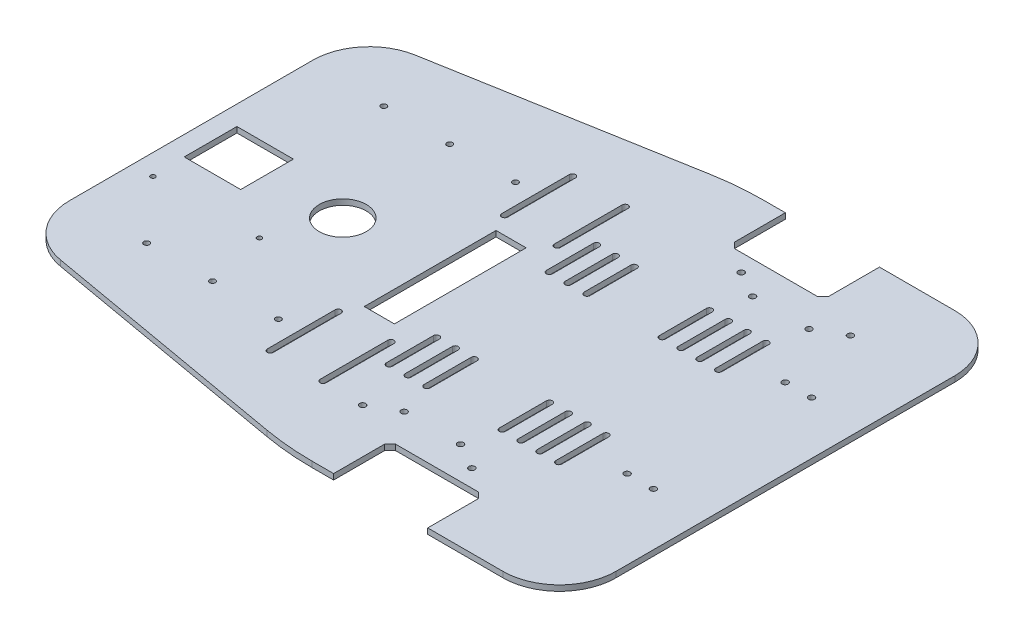
SolidWorks part; units mm, degrees
ref_plane "前视基准面" through (0, 0, 0) normal (0, 0, 1) x (1, 0, 0)
ref_plane "上视基准面" through (0, 0, 0) normal (0, 1, 0) x (1, 0, 0)
ref_plane "右视基准面" through (0, 0, 0) normal (1, 0, 0) x (0, 0, -1)
other "Configuration Table"
sketch "草图1" plane through (0, 0, 0) normal (0, 1, 0) x (1, 0, 0)
  line L0 (40, 120) -> (40, -12.8004) construction
  line L1 (15.3051, 120) -> (130, 120)
  line L2 (-155.7144, 64.6716) -> (-155.7144, -64.6716)
  line L3 (15.3051, -120) -> (130, -120)
  line L4 (160, 90) -> (160, -90)
  line L5 (-160, 120) -> (160, -120) construction
  line L6 (-160, -120) -> (160, 120) construction
  line L7 (15.3051, 120) -> (-130.9239, 94.2159)
  line L8 (-96.2123, 0) -> (107.3836, 0) construction
  line L9 (15.3051, -120) -> (-130.9239, -94.2159)
  arc A0 (130, -120) -> (160, -90) centre (130, -90) ccw
  arc A1 (160, 90) -> (130, 120) centre (130, 90) ccw
  arc A2 (-130.9239, -94.2159) -> (-155.7144, -64.6716) centre (-125.7144, -64.6716) cw
  arc A3 (-155.7144, 64.6716) -> (-130.9239, 94.2159) centre (-125.7144, 64.6716) cw
  point P0 (0, 0)
  point P22 (-155.7144, -89.8446)
  point P25 (-155.7144, 89.8446)
  dimension "D3" = 30
  dimension "D6" = 30
  dimension "D1" = 320
  dimension "D2" = 240
  dimension "D4" = 120
  dimension "D5" = 10
extrude "凸台-拉伸1" add sketch "草图1" along normal blind 3
sketch "草图2" plane through (0, 3, 0) normal (0, 1, 0) x (1, 0, 0)
  line L0 (65, 124.0473) -> (65, -125.6765) construction
  line L1 (160, -90) -> (160, 90) construction
  line L2 (40, -90) -> (90, -90)
  line L4 (15.3051, -120) -> (130, -120) construction
  line L5 (40, -90) -> (40, -120)
  line L6 (40, -120) -> (90, -120)
  line L7 (90, -120) -> (90, -90)
  line L8 (-190.597, 0) -> (207.9466, 0) construction
  line L9 (40, 120) -> (90, 120)
  line L10 (90, 120) -> (90, 90)
  line L11 (40, 90) -> (90, 90)
  line L12 (40, 90) -> (40, 120)
  point P8 (65, -90)
  dimension "D1" = 95
  dimension "D2" = 50
  dimension "D3" = 30
extrude "切除-拉伸1" cut sketch "草图2" against normal through all
chamfer "倒角1" distance 3 angle 45 4 edges at (90, 1.5, -90) (40, 1.5, -90) (90, 1.5, 90) (40, 1.5, 90)
sketch "草图3" plane through (0, 3, 0) normal (0, 1, 0) x (1, 0, 0)
  line L0 (87, -90) -> (43, -90) construction
  line L1 (90, -120) -> (90, -93) construction
  line L2 (45.23, -47.1241) -> (45.23, -105.6682) construction
  line L3 (40, 120) -> (40, 93) construction
  line L4 (43, 90) -> (87, 90) construction
  line L5 (84.77, 111.6004) -> (84.77, 44.6968) construction
  circle A0 centre (74.23, -80.8) radius 1.6
  circle A1 centre (60.23, -72.8) radius 1.6
  circle A2 centre (16.23, -80.8) radius 1.6
  circle A3 centre (30.23, -72.8) radius 1.6
  circle A4 centre (55.77, 80.8) radius 1.6
  circle A5 centre (69.77, 72.8) radius 1.6
  circle A6 centre (99.77, 72.8) radius 1.6
  circle A7 centre (113.77, 80.8) radius 1.6
  dimension "D1" = 9.2
  dimension "D3" = 8
  dimension "D6" = 15.77
  dimension "D8" = 14
  dimension "D2" = 15.77
  dimension "D4" = 14
  dimension "D5" = 15
  dimension "D7" = 9.2
  dimension "D9" = 8
  dimension "D10" = 15
extrude "切除-拉伸2" cut sketch "草图3" against normal through all
fillet "圆角3" radius 150 2 edges at (15.3051, 1.5, 120) (15.3051, 1.5, -120)
sketch "草图6" plane through (0, 3, 0) normal (0, 1, 0) x (1, 0, 0)
  circle A0 centre (132, 41.9099) radius 1.6 construction
  circle A1 centre (118, 41.9099) radius 1.6 construction
  circle A2 centre (132, -42.0901) radius 1.6 construction
  circle A3 centre (118, -42.0901) radius 1.6 construction
  circle A10 centre (132, 41.9099) radius 1.6
  circle A11 centre (118, 41.9099) radius 1.6
  circle A12 centre (132, -42.0901) radius 1.6
  circle A13 centre (118, -42.0901) radius 1.6
extrude "切除-拉伸3" cut sketch "草图6" against normal up to next
sketch "草图8" plane through (0, 0, 0) normal (0, -1, 0) x (1, 0, 0)
  circle A0 centre (-115.7144, -62.381) radius 1.5 construction
  circle A1 centre (-80.7144, -62.381) radius 1.5 construction
  circle A2 centre (-45.7144, -62.381) radius 1.5 construction
  circle A3 centre (-45.7144, 63.619) radius 1.5 construction
  circle A4 centre (-80.7144, 63.619) radius 1.5 construction
  circle A5 centre (-115.7144, 63.619) radius 1.5 construction
  circle A6 centre (-115.7144, -62.381) radius 1.5
  circle A7 centre (-80.7144, -62.381) radius 1.5
  circle A8 centre (-45.7144, -62.381) radius 1.5
  circle A9 centre (-45.7144, 63.619) radius 1.5
  circle A10 centre (-80.7144, 63.619) radius 1.5
  circle A11 centre (-115.7144, 63.619) radius 1.5
extrude "切除-拉伸5" cut sketch "草图8" against normal up to next
sketch "草图11" plane through (0, 0, 0) normal (0, -1, 0) x (1, 0, 0)
  line L0 (-136.2017, 0) -> (170.3375, 0) construction
  line L1 (84.6466, 55) -> (84.6466, 30) construction
  line L2 (86.2466, 55) -> (86.2466, 30)
  line L3 (83.0466, 55) -> (83.0466, 30)
  line L4 (74.6466, 55) -> (74.6466, 30) construction
  line L5 (44.6466, 64.0776) -> (44.6466, 7.7798) construction
  line L6 (4.6466, 55) -> (4.6466, 30) construction
  line L9 (76.2466, 55) -> (76.2466, 30)
  line L10 (73.0466, 55) -> (73.0466, 30)
  line L11 (64.6466, 55) -> (64.6466, 30) construction
  line L12 (66.2466, 55) -> (66.2466, 30)
  line L13 (63.0466, 55) -> (63.0466, 30)
  line L14 (3.0466, 55) -> (3.0466, 30)
  line L15 (6.2466, 55) -> (6.2466, 30)
  line L16 (14.6466, 55) -> (14.6466, 30) construction
  line L17 (13.0466, 55) -> (13.0466, 30)
  line L18 (16.2466, 55) -> (16.2466, 30)
  line L19 (24.6466, 55) -> (24.6466, 30) construction
  line L20 (23.0466, 55) -> (23.0466, 30)
  line L21 (26.2466, 55) -> (26.2466, 30)
  line L22 (4.6466, -55) -> (4.6466, -30) construction
  line L23 (3.0466, -55) -> (3.0466, -30)
  line L24 (6.2466, -55) -> (6.2466, -30)
  line L25 (14.6466, -55) -> (14.6466, -30) construction
  line L26 (13.0466, -55) -> (13.0466, -30)
  line L27 (16.2466, -55) -> (16.2466, -30)
  line L28 (24.6466, -55) -> (24.6466, -30) construction
  line L29 (23.0466, -55) -> (23.0466, -30)
  line L30 (26.2466, -55) -> (26.2466, -30)
  line L31 (84.6466, -55) -> (84.6466, -30) construction
  line L32 (86.2466, -55) -> (86.2466, -30)
  line L33 (83.0466, -55) -> (83.0466, -30)
  line L34 (74.6466, -55) -> (74.6466, -30) construction
  line L35 (76.2466, -55) -> (76.2466, -30)
  line L36 (73.0466, -55) -> (73.0466, -30)
  line L37 (64.6466, -55) -> (64.6466, -30) construction
  line L38 (66.2466, -55) -> (66.2466, -30)
  line L39 (63.0466, -55) -> (63.0466, -30)
  line L40 (94.6466, 55) -> (94.6466, 30) construction
  line L41 (96.2466, 55) -> (96.2466, 30)
  line L42 (93.0466, 55) -> (93.0466, 30)
  line L43 (94.6466, -55) -> (94.6466, -30) construction
  line L44 (96.2466, -55) -> (96.2466, -30)
  line L45 (93.0466, -55) -> (93.0466, -30)
  arc A0 (86.2466, 55) -> (83.0466, 55) centre (84.6466, 55) ccw
  arc A1 (83.0466, 30) -> (86.2466, 30) centre (84.6466, 30) ccw
  arc A4 (76.2466, 55) -> (73.0466, 55) centre (74.6466, 55) ccw
  arc A5 (73.0466, 30) -> (76.2466, 30) centre (74.6466, 30) ccw
  arc A6 (66.2466, 55) -> (63.0466, 55) centre (64.6466, 55) ccw
  arc A7 (63.0466, 30) -> (66.2466, 30) centre (64.6466, 30) ccw
  arc A8 (3.0466, 55) -> (6.2466, 55) centre (4.6466, 55) cw
  arc A9 (6.2466, 30) -> (3.0466, 30) centre (4.6466, 30) cw
  arc A10 (13.0466, 55) -> (16.2466, 55) centre (14.6466, 55) cw
  arc A11 (16.2466, 30) -> (13.0466, 30) centre (14.6466, 30) cw
  arc A12 (23.0466, 55) -> (26.2466, 55) centre (24.6466, 55) cw
  arc A13 (26.2466, 30) -> (23.0466, 30) centre (24.6466, 30) cw
  arc A14 (3.0466, -55) -> (6.2466, -55) centre (4.6466, -55) ccw
  arc A15 (6.2466, -30) -> (3.0466, -30) centre (4.6466, -30) ccw
  arc A16 (13.0466, -55) -> (16.2466, -55) centre (14.6466, -55) ccw
  arc A17 (16.2466, -30) -> (13.0466, -30) centre (14.6466, -30) ccw
  arc A18 (23.0466, -55) -> (26.2466, -55) centre (24.6466, -55) ccw
  arc A19 (26.2466, -30) -> (23.0466, -30) centre (24.6466, -30) ccw
  arc A20 (86.2466, -55) -> (83.0466, -55) centre (84.6466, -55) cw
  arc A21 (83.0466, -30) -> (86.2466, -30) centre (84.6466, -30) cw
  arc A22 (76.2466, -55) -> (73.0466, -55) centre (74.6466, -55) cw
  arc A23 (73.0466, -30) -> (76.2466, -30) centre (74.6466, -30) cw
  arc A24 (66.2466, -55) -> (63.0466, -55) centre (64.6466, -55) cw
  arc A25 (63.0466, -30) -> (66.2466, -30) centre (64.6466, -30) cw
  arc A26 (96.2466, 55) -> (93.0466, 55) centre (94.6466, 55) ccw
  arc A27 (93.0466, 30) -> (96.2466, 30) centre (94.6466, 30) ccw
  arc A28 (96.2466, -55) -> (93.0466, -55) centre (94.6466, -55) cw
  arc A29 (93.0466, -30) -> (96.2466, -30) centre (94.6466, -30) cw
  point P5 (84.6466, 42.5)
  point P15 (4.6466, 42.5)
  point P22 (74.6466, 42.5)
  point P29 (64.6466, 42.5)
  point P35 (14.6466, 42.5)
  point P42 (24.6466, 42.5)
  point P49 (4.6466, -42.5)
  point P56 (14.6466, -42.5)
  point P63 (24.6466, -42.5)
  point P70 (84.6466, -42.5)
  point P77 (74.6466, -42.5)
  point P84 (64.6466, -42.5)
  point P93 (94.6466, 42.5)
  point P100 (94.6466, -42.5)
  dimension "D1" = 1.6
  dimension "D2" = 3
  dimension "D3" = 25
  dimension "D4" = 55
  dimension "D5" = 40
  dimension "D6" = 2
extrude "切除-拉伸11" cut sketch "草图11" against normal up to next
sketch "草图12" plane through (0, 0, 0) normal (0, -1, 0) x (1, 0, 0)
  line L0 (-136.8905, 0) -> (128.3175, 0) construction
  line L2 (-28.7041, 35) -> (-12.7041, 35)
  line L3 (-28.7041, 35) -> (-28.7041, -35)
  line L4 (-28.7041, -35) -> (-12.7041, -35)
  line L5 (-12.7041, 35) -> (-12.7041, -35)
  line L6 (-28.7041, 35) -> (-12.7041, -35) construction
  line L7 (-28.7041, -35) -> (-12.7041, 35) construction
  circle A0 centre (-75.1234, 0) radius 12.5
  point P5 (-20.7041, 0)
  dimension "D1" = 25
  dimension "D2" = 70
  dimension "D3" = 16
extrude "切除-拉伸12" cut sketch "草图12" against normal up to next
sketch "草图13" plane through (0, 3, 0) normal (0, 1, 0) x (1, 0, 0)
  line L0 (-115.3644, -14) -> (-115.3644, 14)
  line L1 (-115.3644, 14) -> (-145.3644, 14)
  line L2 (-145.3644, 14) -> (-145.3644, -14)
  line L4 (-145.3644, -14) -> (-115.3644, -14)
  line L5 (0, 0) -> (-168.5777, 0) construction
  line L6 (-136.9144, -22.8) -> (-136.9144, -14.9) construction
  dimension "D1" = 14
  dimension "D2" = 8.45
  dimension "D3" = 14
  dimension "D4" = 30
extrude "切除-拉伸13" cut sketch "草图13" against normal up to next
sketch "草图14" plane through (0, 3, 0) normal (0, 1, 0) x (1, 0, 0)
  circle A0 centre (-144.7144, -31.3) radius 1.25 construction
  circle A1 centre (-88.1144, -31.3) radius 1.25 construction
  circle A2 centre (-144.7144, -31.3) radius 1.25
  circle A3 centre (-88.1144, -31.3) radius 1.25
sketch "草图15" plane through (0, 3, 0) normal (0, 1, 0) x (1, 0, 0)
  circle A0 centre (-144.7144, -31.3) radius 1.25
  circle A1 centre (-88.1144, -31.3) radius 1.25
extrude "切除-拉伸16" cut sketch "草图15" against normal blind 8
sketch "草图18" plane through (0, 3, 0) normal (0, 1, 0) x (1, 0, 0)
  circle A0 centre (-5.3574, -80.2401) radius 1.6 construction
  circle A1 centre (-5.3574, -52.2401) radius 1.6 construction
  circle A2 centre (-33.3574, -80.2401) radius 1.6 construction
  circle A3 centre (-33.3574, -52.2401) radius 1.6 construction
  circle A4 centre (-5.3574, -80.2401) radius 1.6
  circle A5 centre (-5.3574, -52.2401) radius 1.6
  circle A6 centre (-33.3574, -80.2401) radius 1.6
  circle A7 centre (-33.3574, -52.2401) radius 1.6
sketch "草图19" plane through (0, 3, 0) normal (0, 1, 0) x (1, 0, 0)
  line L0 (-33.3574, -44.2401) -> (-33.3574, -80.2401) construction
  line L1 (-31.7574, -44.2401) -> (-31.7574, -80.2401)
  line L2 (-34.9574, -44.2401) -> (-34.9574, -80.2401)
  line L3 (-33.3574, -80.2401) -> (-5.3574, -80.2401) construction
  line L4 (-19.3574, -80.2401) -> (-19.3574, -88.0016) construction
  line L5 (-5.3574, -44.2401) -> (-5.3574, -80.2401) construction
  line L6 (-6.9574, -44.2401) -> (-6.9574, -80.2401)
  line L7 (-3.7574, -44.2401) -> (-3.7574, -80.2401)
  arc A0 (-31.7574, -44.2401) -> (-34.9574, -44.2401) centre (-33.3574, -44.2401) ccw
  arc A1 (-34.9574, -80.2401) -> (-31.7574, -80.2401) centre (-33.3574, -80.2401) ccw
  arc A2 (-6.9574, -44.2401) -> (-3.7574, -44.2401) centre (-5.3574, -44.2401) cw
  arc A3 (-3.7574, -80.2401) -> (-6.9574, -80.2401) centre (-5.3574, -80.2401) cw
  point P4 (-33.3574, -62.2401)
  point P15 (-5.3574, -62.2401)
  dimension "D1" = 1.6
  dimension "D2" = 36
extrude "切除-拉伸17" cut sketch "草图19" against normal blind 10
mirror "镜向1" about plane through (0, 0, 0) normal (0, 0, 1) of "切除-拉伸17"
